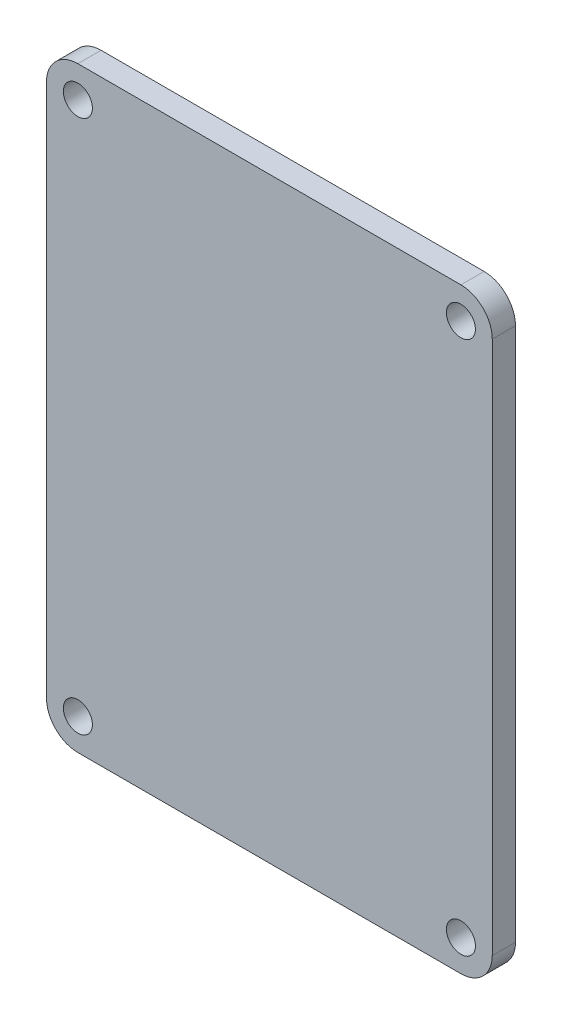
SolidWorks part; units mm, degrees
ref_plane "Front Plane" through (0, 0, 0) normal (0, 0, 1) x (1, 0, 0)
ref_plane "Top Plane" through (0, 0, 0) normal (0, 1, 0) x (1, 0, 0)
ref_plane "Right Plane" through (0, 0, 0) normal (1, 0, 0) x (0, 0, -1)
ref_plane "Plane1" through (0, 0, 3.5791) normal (0, 0, 1) x (1, 0, 0)
sketch "Sketch1" plane through (0, 0, 3.5791) normal (0, 0, 1) x (1, 0, 0)
  line L0 (-22.5383, 18.4513) -> (-22.5383, -27.5487) construction
  line L1 (13.4617, 21.4513) -> (-19.5383, 21.4513) construction
  line L2 (-22.5383, 18.4513) -> (-22.5383, 17.4736)
  line L3 (-18.5606, 21.4513) -> (-19.5383, 21.4513)
  line L4 (-22.5383, 18.4513) -> (-22.5383, 17.4736) construction
  line L5 (-18.5606, 21.4513) -> (-19.5383, 21.4513) construction
  line L6 (16.4617, -27.5487) -> (16.4617, 18.4513) construction
  line L7 (-19.5383, -30.5487) -> (13.4617, -30.5487) construction
  line L8 (-22.5383, 18.4513) -> (-22.5383, -27.5487) construction
  line L9 (13.4617, 21.4513) -> (-19.5383, 21.4513) construction
  line L10 (16.4617, -27.5487) -> (16.4617, 18.4513) construction
  line L11 (-19.5383, -30.5487) -> (13.4617, -30.5487) construction
  line L12 (-18.5606, 21.1513) -> (-19.5383, 21.1513)
  line L13 (-22.2383, 18.4513) -> (-22.2383, 17.4736)
  line L14 (-22.2383, 18.4513) -> (-22.2383, -27.5487)
  line L15 (-19.5383, -30.2487) -> (13.4617, -30.2487)
  line L16 (16.1617, -27.5487) -> (16.1617, 18.4513)
  line L17 (13.4617, 21.1513) -> (-19.5383, 21.1513)
  arc A0 (-22.5383, -27.5487) -> (-19.5383, -30.5487) centre (-19.5383, -27.5487) ccw construction
  arc A1 (-19.5383, 21.4513) -> (-22.5383, 18.4513) centre (-19.5383, 18.4513) ccw construction
  arc A2 (-19.5383, 21.4513) -> (-22.5383, 18.4513) centre (-19.5383, 18.4513) ccw
  arc A3 (-22.5383, 17.4736) -> (-18.5606, 21.4513) centre (-19.5383, 18.4513) ccw
  arc A4 (-19.5383, 21.4513) -> (-22.5383, 18.4513) centre (-19.5383, 18.4513) ccw construction
  arc A6 (16.4617, 18.4513) -> (13.4617, 21.4513) centre (13.4617, 18.4513) ccw construction
  arc A7 (13.4617, -30.5487) -> (16.4617, -27.5487) centre (13.4617, -27.5487) ccw construction
  arc A8 (-22.5383, -27.5487) -> (-19.5383, -30.5487) centre (-19.5383, -27.5487) ccw construction
  arc A9 (-19.5383, 21.4513) -> (-22.5383, 18.4513) centre (-19.5383, 18.4513) ccw construction
  arc A10 (16.4617, 18.4513) -> (13.4617, 21.4513) centre (13.4617, 18.4513) ccw construction
  arc A11 (13.4617, -30.5487) -> (16.4617, -27.5487) centre (13.4617, -27.5487) ccw construction
  arc A12 (-19.5383, 21.1513) -> (-22.2383, 18.4513) centre (-19.5383, 18.4513) ccw
  arc A13 (-22.2383, -27.5487) -> (-19.5383, -30.2487) centre (-19.5383, -27.5487) ccw
  arc A14 (13.4617, -30.2487) -> (16.1617, -27.5487) centre (13.4617, -27.5487) ccw
  arc A15 (16.1617, 18.4513) -> (13.4617, 21.1513) centre (13.4617, 18.4513) ccw
  arc A16 (-19.5383, 21.1513) -> (-22.2383, 18.4513) centre (-19.5383, 18.4513) ccw
  point P0 (13.4617, -27.5487)
  point P2 (-19.5383, -27.5487)
  dimension "D1" = 0
  dimension "D2" = 0.3
extrude "Boss-Extrude1" add sketch "Sketch1" along normal blind 2 contours L16 A15 L17 L12 A12 L13 L14 A13 L15 A14
hole_wizard "M3 Tapped Hole1" positions "Sketch2" profile "Sketch4" tap size "M3" standard "ISO"
sketch "Sketch2" plane through (0, 0, 3.5791) normal (0, 0, -1) x (-1, 0, 0)
  point P0 (19.5383, 18.4513)
  point P3 (-13.4617, 18.4513)
  point P6 (-13.4617, -27.5487)
  point P9 (19.5383, -27.5487)
sketch "Sketch4" plane through (-19.5383, 18.4513, 3.5791) normal (1, 0, 0) x (0, 1, 0)
  line L0 (0, 0) -> (0, 8.2511)
  line L1 (0, 8.2511) -> (1.25, 7.5)
  line L2 (1.25, 7.5) -> (1.25, 0)
  line L5 (1.25, 0) -> (0, 0)
  line L10 (0, 8.2511) -> (-1.25, 7.5) construction
  line L11 (0, -6.35) -> (0, 107.95) construction
  dimension "Tap Drill Dia." = 2.5
  dimension "Tap Drill Depth" = 7.5
  dimension "Drill Angle" = 118
cosmetic thread "Hole Thread1" parameters "D1"=6, "D2"=3
cosmetic thread "Hole Thread2" parameters "D1"=6, "D2"=3
cosmetic thread "Hole Thread3" parameters "D1"=6, "D2"=3
cosmetic thread "Hole Thread4" parameters "D1"=6, "D2"=3
sketch "Sketch5" plane through (0, 0, 3.5791) normal (0, 0, -1) x (-1, 0, 0)
  circle A0 centre (3.0383, 4.4513) radius 3 construction
  circle A1 centre (3.0383, 4.4513) radius 3 construction
  circle A2 centre (3.0383, 4.4513) radius 4
  dimension "D1" = 1
extrude "Cut-Extrude4" cut sketch "Sketch5" against normal blind 0.6 contours A2
